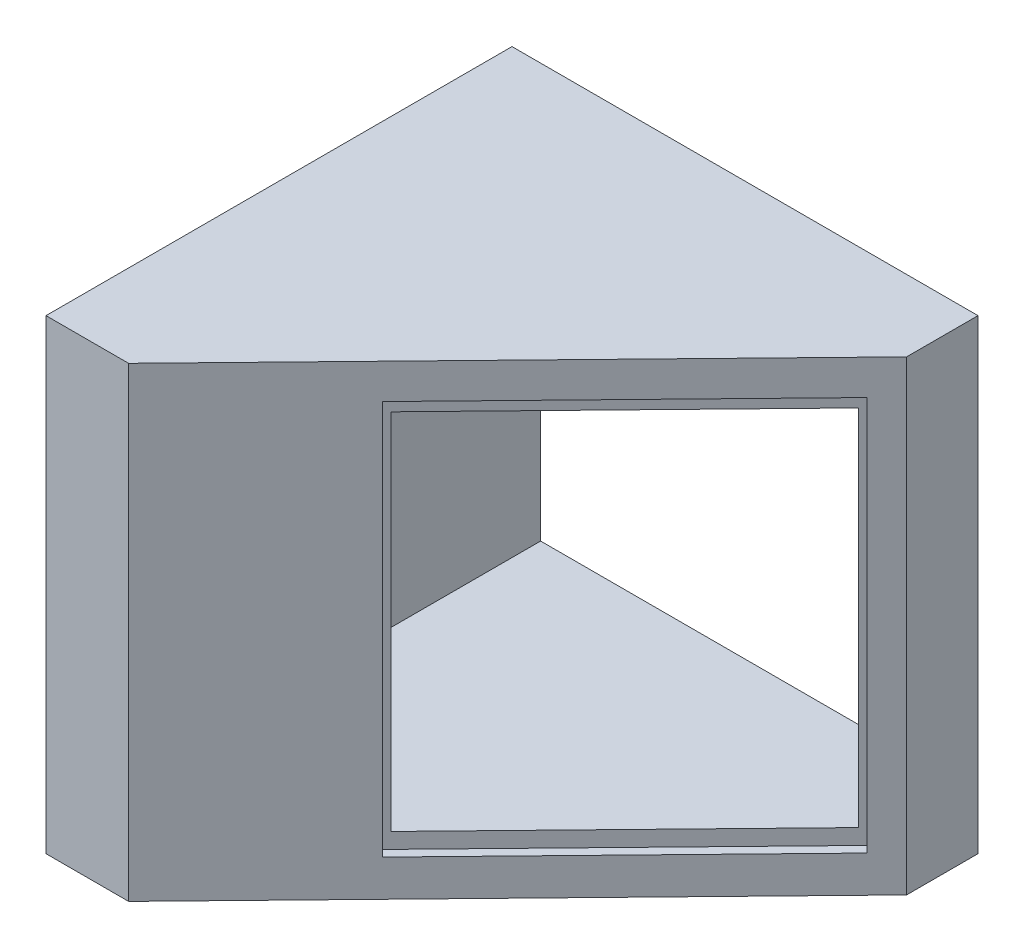
SolidWorks part; units mm, degrees
ref_plane "Front Plane" through (0, 0, 0) normal (0, 0, 1) x (1, 0, 0)
ref_plane "Top Plane" through (0, 0, 0) normal (0, 1, 0) x (1, 0, 0)
ref_plane "Right Plane" through (0, 0, 0) normal (1, 0, 0) x (0, 0, -1)
sketch "Sketch3" plane through (0, 0, 0) normal (0, 0, 1) x (1, 0, 0)
  line L1 (-88.7126, 70.7407) -> (61.2874, 70.7407)
  line L2 (-88.7126, 70.7407) -> (-88.7126, -79.2593)
  line L3 (-88.7126, -79.2593) -> (61.2874, -79.2593)
  line L4 (61.2874, 70.7407) -> (61.2874, -79.2593)
  dimension "D1" = 150
  dimension "D2" = 150
extrude "Boss-Extrude2" add sketch "Sketch3" along normal blind 150
sketch "Sketch6" plane through (0, -79.2593, 0) normal (0, -1, 0) x (1, 0, 0)
  line L0 (61.2874, 22.9753) -> (-62.1173, 150)
  line L1 (61.2874, 150) -> (61.2874, 0) construction
  line L2 (-88.7126, 150) -> (61.2874, 150) construction
  line L3 (-62.1173, 150) -> (61.2874, 150)
  line L4 (61.2874, 150) -> (61.2874, 22.9753)
extrude "Cut-Extrude3" cut sketch "Sketch6" against normal blind 150
sketch "Sketch8" plane through (0, 0, 0) normal (0, 0, -1) x (-1, 0, 0)
  line L1 (-51.5509, 54.4883) -> (79.4934, 54.4883)
  line L2 (-51.5509, 54.4883) -> (-51.5509, -62.4897)
  line L3 (-51.5509, -62.4897) -> (79.4934, -62.4897)
  line L4 (79.4934, 54.4883) -> (79.4934, -62.4897)
  point P4 (74.1151, 44.8694)
  point P5 (75.5631, 30.5963)
  point P6 (-51.1372, 54.2815)
extrude "Cut-Extrude7" cut sketch "Sketch8" against normal blind 105
sketch "Sketch9" plane through (43.0123, 0, 41.7865) normal (0.7173, 0, 0.6968) x (0.6968, 0, -0.7173)
  line L1 (-88.1328, -62.4897) -> (-93.0876, -62.4897)
  line L2 (-88.1328, -62.4897) -> (-88.1328, 54.4883)
  line L3 (-88.1328, 54.4883) -> (-93.0876, 54.4883)
  line L4 (-93.0876, -62.4897) -> (-93.0876, 54.4883)
extrude "Cut-Extrude10" cut sketch "Sketch9" against normal blind 3
sketch "Sketch10" plane through (43.0123, 0, 41.7865) normal (0.7173, 0, 0.6968) x (0.6968, 0, -0.7173)
  line L1 (-93.0876, -62.4897) -> (12.2539, -62.4897)
  line L2 (-93.0876, -62.4897) -> (-93.0876, -67.4897)
  line L3 (-93.0876, -67.4897) -> (12.2539, -67.4897)
  line L4 (12.2539, -62.4897) -> (12.2539, -67.4897)
  dimension "D1" = 5
extrude "Cut-Extrude12" cut sketch "Sketch10" against normal blind 3
sketch "Sketch11" plane through (43.0123, 0, 41.7865) normal (0.7173, 0, 0.6968) x (0.6968, 0, -0.7173)
  line L1 (12.2539, -67.4897) -> (17.2539, -67.4897)
  line L2 (12.2539, -67.4897) -> (12.2539, 54.4883)
  line L3 (12.2539, 54.4883) -> (17.2539, 54.4883)
  line L4 (17.2539, -67.4897) -> (17.2539, 54.4883)
  dimension "D1" = 5
extrude "Cut-Extrude13" cut sketch "Sketch11" against normal blind 3
sketch "Sketch12" plane through (43.0123, 0, 41.7865) normal (0.7173, 0, 0.6968) x (0.6968, 0, -0.7173)
  line L1 (17.2539, 54.4883) -> (-93.0876, 54.4883)
  line L2 (17.2539, 54.4883) -> (17.2539, 59.4883)
  line L3 (17.2539, 59.4883) -> (-93.0876, 59.4883)
  line L4 (-93.0876, 54.4883) -> (-93.0876, 59.4883)
  dimension "D1" = 5
extrude "Cut-Extrude14" cut sketch "Sketch12" against normal blind 3
